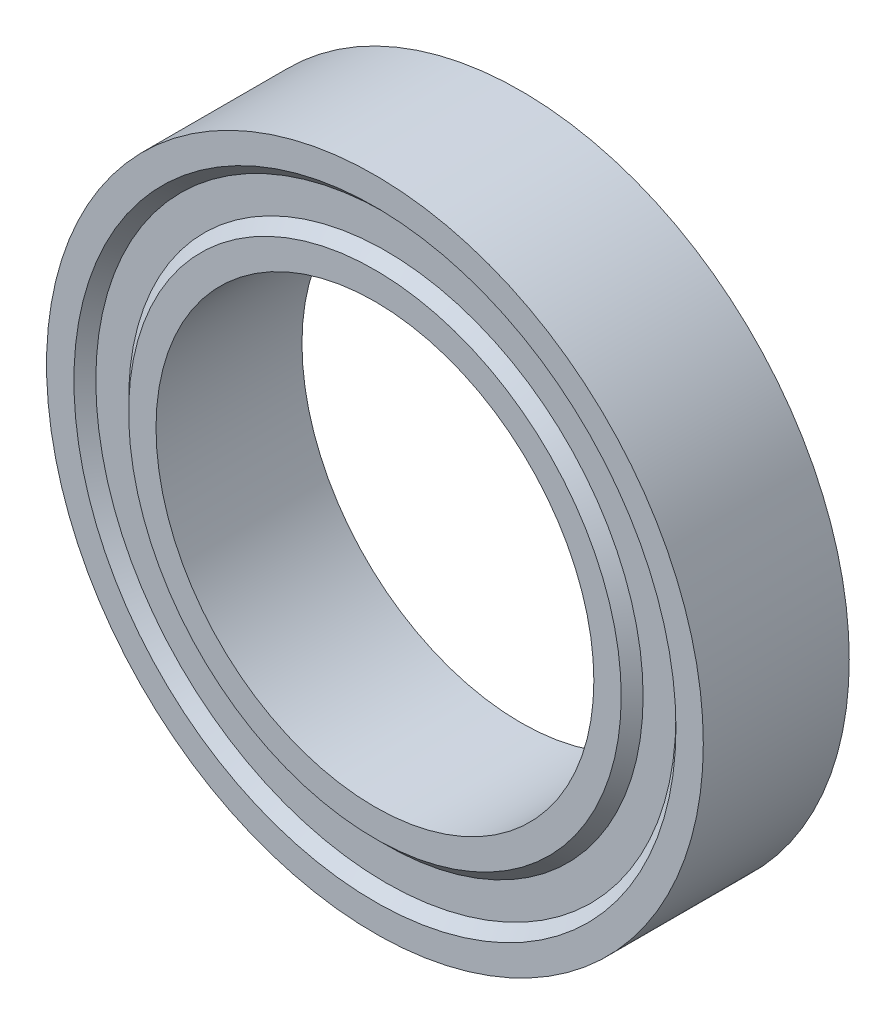
SolidWorks part; units mm, degrees
ref_plane "Front Plane" through (0, 0, 0) normal (0, 0, 1) x (1, 0, 0)
ref_plane "Top Plane" through (0, 0, 0) normal (0, 1, 0) x (1, 0, 0)
ref_plane "Right Plane" through (0, 0, 0) normal (1, 0, 0) x (0, 0, -1)
sketch "Sketch1" plane through (0, 0, 0) normal (0, 1, 0) x (1, 0, 0)
  line L0 (0, 0) -> (6, 0) construction
  line L1 (6, -2) -> (6, 2)
  line L2 (6, 2) -> (6.75, 2)
  line L3 (6.75, 2) -> (7.05, 1.7)
  line L4 (7.05, 1.7) -> (7.95, 1.7)
  line L5 (7.95, 1.7) -> (8.25, 2)
  line L6 (8.25, 2) -> (9, 2)
  line L7 (9, 2) -> (9, -2)
  line L8 (9, 0) -> (6, 0) construction
  line L9 (8.25, -2) -> (9, -2)
  line L10 (7.95, -1.7) -> (8.25, -2)
  line L11 (7.05, -1.7) -> (7.95, -1.7)
  line L12 (6.75, -2) -> (7.05, -1.7)
  line L13 (6, -2) -> (6.75, -2)
  line L14 (0, 0) -> (0, 2) construction
  dimension "D1" = 6
  dimension "D2" = 9
  dimension "D3" = 2
  dimension "D4" = 0.3
  dimension "D5" = 0.75
revolve "Revolve1" add sketch "Sketch1" angle 360 about L14
